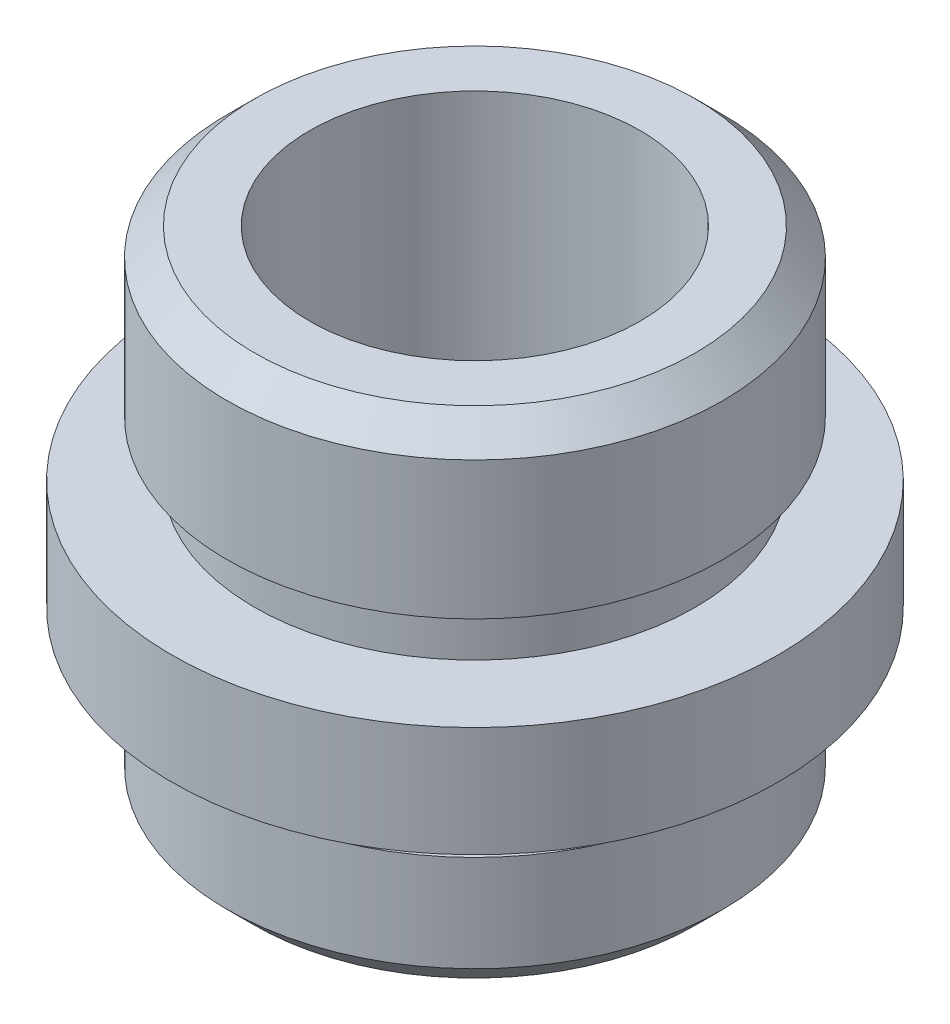
SolidWorks part; units mm, degrees
ref_plane "Front Plane" through (0, 0, 0) normal (0, 0, 1) x (1, 0, 0)
ref_plane "Top Plane" through (0, 0, 0) normal (0, 1, 0) x (1, 0, 0)
ref_plane "Right Plane" through (0, 0, 0) normal (1, 0, 0) x (0, 0, -1)
sketch "Sketch1" plane through (0, 0, 0) normal (0, 0, 1) x (1, 0, 0)
  line L0 (-12, 0) -> (-12, -36)
  line L1 (-12, 0) -> (-16, 0)
  line L2 (-18, -2) -> (-18, -12)
  line L3 (-18, -12) -> (-16, -12)
  line L4 (-16, -12) -> (-16, -16)
  line L5 (-16, -16) -> (-22, -16)
  line L6 (-22, -16) -> (-22, -24)
  line L7 (-22, -24) -> (-16, -24)
  line L9 (-16, -24) -> (-16, -27)
  line L10 (-16, -27) -> (-18, -27)
  line L11 (-18, -27) -> (-18, -34)
  line L12 (-16, -36) -> (-12, -36)
  line L13 (0, -1000) -> (0, 49000) construction
  line L14 (-1000, 0) -> (49000, 0) construction
  line L15 (-16, 0) -> (-18, -2)
  line L16 (-18, -34) -> (-16, -36)
  point P4 (-18, 0)
  point P15 (-18, -36)
  dimension "D2" = 12
  dimension "D3" = 18
  dimension "D4" = 22
  dimension "D5" = 16
  dimension "D6" = 36
  dimension "D7" = 12
  dimension "D8" = 3
  dimension "D9" = 4
  dimension "D10" = 12
  dimension "D11" = 16
revolve "Revolve2" add sketch "Sketch1" angle 360 about L13
